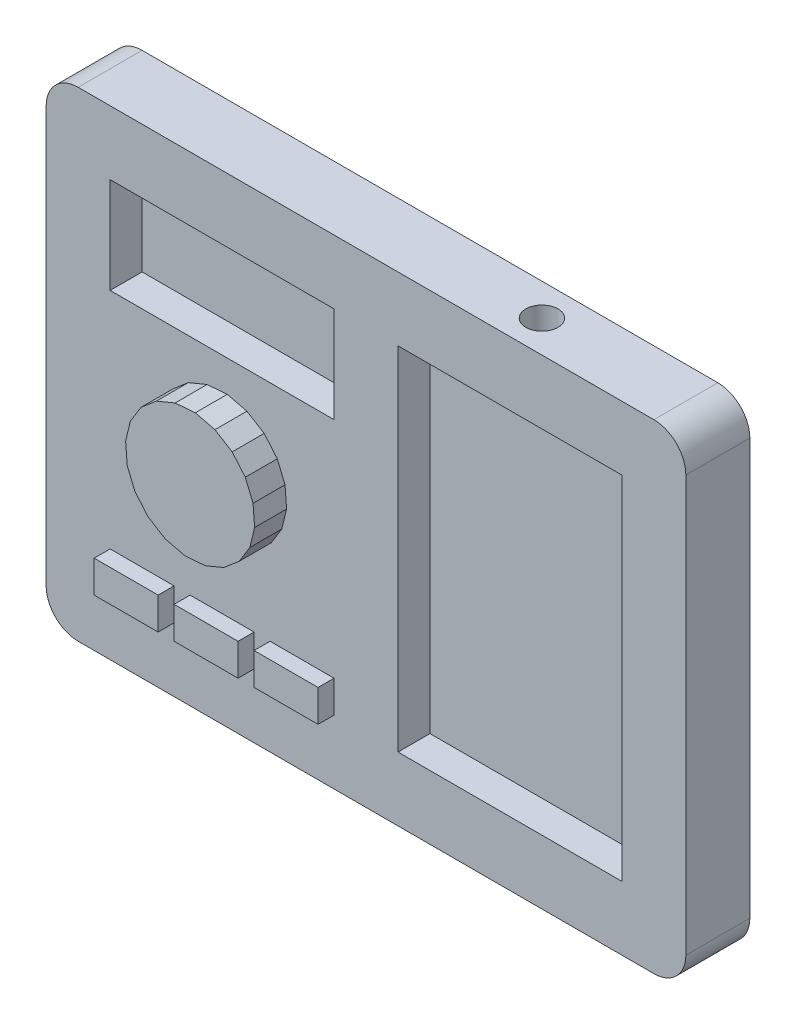
SolidWorks part; units mm, degrees
ref_plane "Front Plane" through (0, 0, 0) normal (0, 0, 1) x (1, 0, 0)
ref_plane "Top Plane" through (0, 0, 0) normal (0, 1, 0) x (1, 0, 0)
ref_plane "Right Plane" through (0, 0, 0) normal (1, 0, 0) x (0, 0, -1)
sketch "Sketch1" plane through (0, 0, 0) normal (0, 0, 1) x (1, 0, 0)
  line L1 (10, 0) -> (190, 0)
  line L2 (0, 10) -> (0, 140)
  line L3 (10, 150) -> (190, 150)
  line L4 (200, 10) -> (200, 140)
  arc A0 (0, 140) -> (10, 150) centre (10, 140) cw
  arc A1 (190, 150) -> (200, 140) centre (190, 140) cw
  arc A2 (10, 0) -> (0, 10) centre (10, 10) cw
  arc A3 (190, 0) -> (200, 10) centre (190, 10) ccw
  point P5 (0, 0)
  point P6 (0, 0)
  point P7 (0, 0)
  point P14 (0, 0)
  dimension "D1" = 10
  dimension "D2" = 10
  dimension "D3" = 10
  dimension "D4" = 10
extrude "Boss-Extrude1" add sketch "Sketch1" along normal blind 20 contours L4 A1 L3 A0 L2 A2 L1 A3
sketch "Sketch2" plane through (0, 0, 20) normal (0, 0, 1) x (1, 0, 0)
  line L0 (110, 20) -> (180, 20)
  line L1 (20, 100) -> (90, 100)
  line L2 (20, 100) -> (20, 130)
  line L3 (20, 130) -> (90, 130)
  line L4 (90, 100) -> (90, 130)
  line L5 (110, 20) -> (110, 130)
  line L6 (110, 130) -> (180, 130)
  line L7 (180, 20) -> (180, 130)
  point P4 (0, 0)
  point P5 (0, 0)
  point P6 (0, 0)
  point P7 (0, 0)
  point P8 (0, 0)
  point P13 (0, 0)
  point P14 (0, 0)
  point P15 (0, 0)
  point P16 (0, 0)
  point P17 (0, 0)
  point P18 (0, 0)
  point P19 (0, 0)
  point P20 (0, 0)
  point P21 (0, 0)
  point P22 (0, 0)
  point P23 (0, 0)
  point P24 (0, 0)
  point P25 (0, 0)
  point P26 (0, 0)
  point P27 (0, 0)
  point P28 (0, 0)
  point P29 (0, 0)
  point P30 (0, 0)
extrude "Cut-Extrude1" cut sketch "Sketch2" against normal blind 10
sketch "Sketch3" plane through (0, 150, 0) normal (0, 1, 0) x (1, 0, 0)
  circle A0 centre (145, -10) radius 5.0227
extrude "Cut-Extrude2" cut sketch "Sketch3" against normal blind 10
sketch "Sketch4" plane through (0, 0, 0) normal (0, -1, 0) x (1, 0, 0)
  line L1 (50, 10) -> (62, 10)
  line L2 (50, 10) -> (50, 5.5)
  line L3 (50, 5.5) -> (62, 5.5)
  line L4 (62, 10) -> (62, 5.5)
  point P4 (0, 0)
  point P5 (0, 0)
  point P6 (0, 0)
  point P7 (0, 0)
  point P8 (0, 0)
  point P9 (0, 0)
  point P10 (0, 0)
  point P11 (0, 0)
  point P12 (0, 0)
extrude "Cut-Extrude3" cut sketch "Sketch4" against normal blind 20
sketch "Sketch5" plane through (0, 0, 20) normal (0, 0, 1) x (1, 0, 0)
  line L0 (68.1586, 85.3632) -> (62.7671, 88.6775)
  line L1 (65.5451, 52.7379) -> (70.3632, 56.8414)
  line L2 (70.3632, 56.8414) -> (73.6775, 62.2329)
  line L3 (73.6775, 62.2329) -> (75.1635, 68.3848)
  line L4 (75.1635, 68.3848) -> (74.6758, 74.6947)
  line L5 (74.6758, 74.6947) -> (72.2621, 80.5451)
  line L6 (72.2621, 80.5451) -> (68.1586, 85.3632)
  line L7 (62.7671, 88.6775) -> (56.6152, 90.1635)
  line L8 (56.6152, 90.1635) -> (50.3053, 89.6758)
  line L9 (50.3053, 89.6758) -> (44.4549, 87.2621)
  line L10 (44.4549, 87.2621) -> (39.6368, 83.1586)
  line L11 (39.6368, 83.1586) -> (36.3225, 77.7671)
  line L12 (36.3225, 77.7671) -> (34.8365, 71.6152)
  line L13 (34.8365, 71.6152) -> (35.3242, 65.3053)
  line L14 (35.3242, 65.3053) -> (37.7379, 59.4549)
  line L15 (37.7379, 59.4549) -> (41.8414, 54.6368)
  line L16 (41.8414, 54.6368) -> (47.2329, 51.3225)
  line L17 (47.2329, 51.3225) -> (53.3848, 49.8365)
  line L18 (53.3848, 49.8365) -> (59.6947, 50.3242)
  line L19 (59.6947, 50.3242) -> (65.5451, 52.7379)
  circle A0 centre (55, 70) radius 19.9791 construction
  point P1 (0, 0)
extrude "Boss-Extrude3" add sketch "Sketch5" along normal blind 10 contours L1 L2 L3 L4 L5 L6 L0 L7 L8 L9 L10 L11 L12 L13 L14 L15 L16 L17 L18 L19
sketch "Sketch6" plane through (0, 0, 20) normal (0, 0, 1) x (1, 0, 0)
  line L1 (20, 30) -> (40, 30)
  line L2 (20, 30) -> (20, 20)
  line L3 (20, 20) -> (40, 20)
  line L4 (40, 30) -> (40, 20)
  line L16 (45, 30) -> (65, 30)
  line L17 (45, 30) -> (45, 20)
  line L18 (45, 20) -> (65, 20)
  line L19 (65, 30) -> (65, 20)
  line L20 (70, 30) -> (90, 30)
  line L21 (70, 30) -> (70, 20)
  line L22 (70, 20) -> (90, 20)
  line L23 (90, 30) -> (90, 20)
  point P4 (0, 0)
  point P6 (0, 0)
  point P8 (0, 0)
  point P9 (0, 0)
  point P16 (0, 0)
  point P17 (0, 0)
  point P18 (0, 0)
  point P19 (0, 0)
  point P20 (0, 0)
  point P21 (0, 0)
  point P22 (0, 0)
  point P23 (0, 0)
  point P24 (0, 0)
  point P25 (0, 0)
  point P26 (0, 0)
  point P27 (0, 0)
  point P28 (0, 0)
  point P29 (0, 0)
  point P30 (0, 0)
  point P31 (0, 0)
extrude "Boss-Extrude4" add sketch "Sketch6" along normal blind 5
